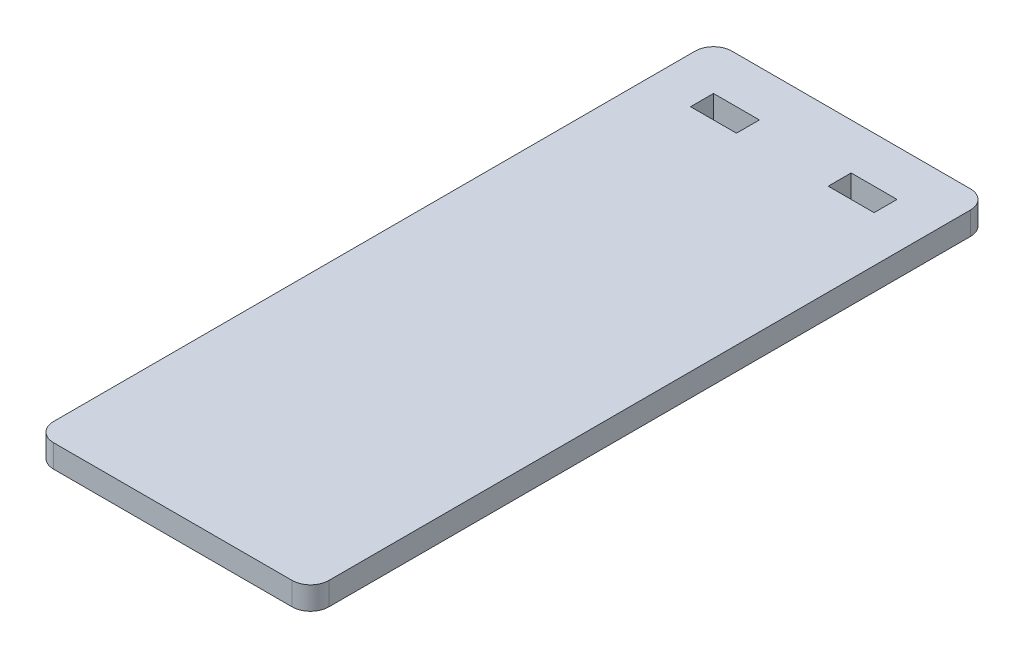
SolidWorks part; units mm, degrees
material "Acrylic (Medium-high impact)"
ref_plane "Front Plane" through (0, 0, 0) normal (0, 0, 1) x (1, 0, 0)
ref_plane "Top Plane" through (0, 0, 0) normal (0, 1, 0) x (1, 0, 0)
ref_plane "Right Plane" through (0, 0, 0) normal (1, 0, 0) x (0, 0, -1)
ref_plane "Plane1" through (0, 0, 0) normal (0, 1, 0) x (1, 0, 0)
sketch "Sketch1" plane through (0, 0, 0) normal (0, 1, 0) x (1, 0, 0)
  line L1 (0, 0) -> (38.1, 0)
  line L2 (0, 0) -> (0, 93.875)
  line L3 (0, 93.875) -> (38.1, 93.875)
  line L4 (38.1, 0) -> (38.1, 93.875)
  dimension "D1" = 38.1
  dimension "D2" = 93.875
extrude "Boss-Extrude1" add sketch "Sketch1" along normal blind 3.175
sketch "Sketch2" plane through (0, 3.175, 0) normal (0, 1, 0) x (1, 0, 0)
  line L0 (38.1, 0) -> (38.1, 93.875) construction
  line L1 (6.35, 87.525) -> (12.7, 87.525)
  line L2 (6.35, 87.525) -> (6.35, 84.35)
  line L3 (6.35, 84.35) -> (12.7, 84.35)
  line L4 (12.7, 87.525) -> (12.7, 84.35)
  line L5 (25.4, 84.35) -> (31.75, 84.35)
  line L6 (38.1, 93.875) -> (0, 93.875) construction
  line L7 (0, 93.875) -> (0, 0) construction
  line L8 (25.4, 84.35) -> (25.4, 87.525)
  line L9 (25.4, 87.525) -> (31.75, 87.525)
  line L10 (31.75, 84.35) -> (31.75, 87.525)
  dimension "D1" = 3.175
  dimension "D2" = 6.35
  dimension "D3" = 6.35
  dimension "D4" = 6.35
  dimension "D5" = 6.35
  dimension "D6" = 6.35
  dimension "D7" = 6.35
  dimension "D8" = 3.175
extrude "Cut-Extrude1" cut sketch "Sketch2" against normal through all
fillet "Fillet1" radius 2.54 4 edges at (38.1, 1.5875, 0) (0, 1.5875, 0) (38.1, 1.5875, -93.875) (0, 1.5875, -93.875)
